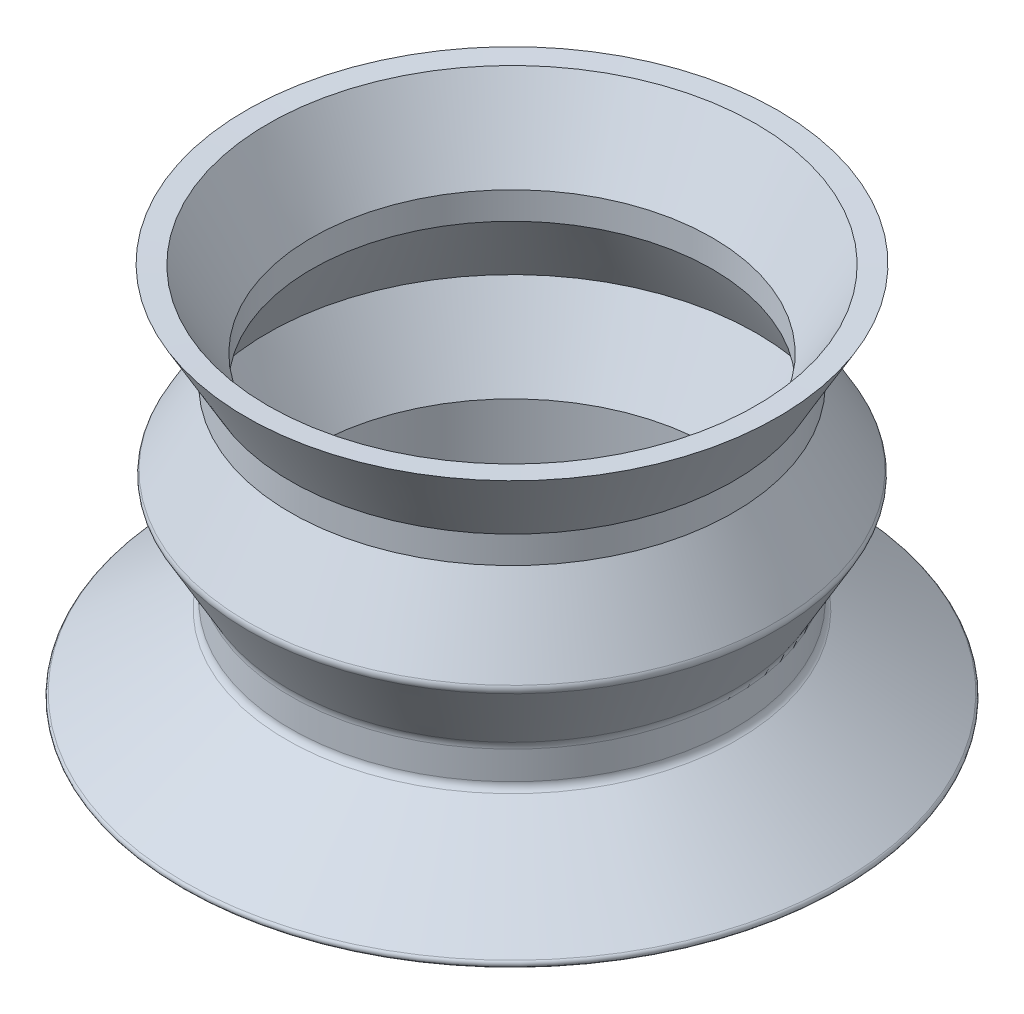
SolidWorks part; units mm, degrees
ref_plane "Front Plane" through (0, 0, 0) normal (0, 0, 1) x (1, 0, 0)
ref_plane "Top Plane" through (0, 0, 0) normal (0, 1, 0) x (1, 0, 0)
ref_plane "Right Plane" through (0, 0, 0) normal (1, 0, 0) x (0, 0, -1)
sketch "Sketch1" plane through (0, 0, 0) normal (0, 0, 1) x (1, 0, 0)
  line L0 (-18, 0) -> (-12, 4.2)
  line L1 (55, 0) -> (-55, 0) construction
  line L5 (-12, 4.2) -> (-11.6848, 3.2) construction
  line L7 (0, -55) -> (0, 55) construction
  line L8 (-18, 0) -> (-11.7545, -4.3719)
  line L12 (-12, 4.2) -> (0, 4.2) construction
  line L13 (-11.7545, -4.3719) -> (0, -4.3719) construction
  line L15 (-16.2562, 0) -> (-11.6848, 3.2)
  line L16 (-11.6848, 3.2) -> (0, 3.2) construction
  line L17 (-16.2562, 0) -> (-11.4393, -3.3719) construction
  line L18 (-11.4393, -3.3719) -> (0, -3.3719) construction
  line L19 (0, 4.2) -> (0, 3.2) construction
  line L20 (-16.2562, 0) -> (-11.4393, -3.3719)
  line L21 (-11.4393, -3.3719) -> (0, -3.3719) construction
  line L22 (-11.4393, -3.3719) -> (-11.7545, -4.3719)
  line L23 (-12, 4.2) -> (-12, 6.2)
  line L24 (-16.2562, 0) -> (-11.6848, 3.2) construction
  line L25 (0, -3.3719) -> (0, -4.3719) construction
  line L27 (-10.8755, 6.2476) -> (-10.8755, 3.2)
  line L28 (-10.8755, 3.2) -> (-11.6848, 3.2)
  line L29 (-10.8755, 3.2) -> (-10.8755, -7.0879) construction
  line L30 (-14.4, 10.4) -> (-12, 6.2)
  line L31 (-14.4, 10.4) -> (-12, 14.6)
  line L32 (-13.2482, 10.4) -> (-10.8755, 6.2476)
  line L33 (-13.2482, 10.4) -> (-10.8482, 14.6)
  line L34 (0, 16.9201) -> (0, 4.5742) construction
  line L35 (-10.8482, 14.6) -> (-10.8482, 16.0759)
  line L37 (-12, 16.0759) -> (-12, 14.6)
  line L38 (-13.221, 20.2283) -> (-10.8482, 16.0759)
  line L39 (-14.4, 20.2759) -> (-12, 16.0759)
  line L40 (-14.4, 20.2759) -> (-13.221, 20.2283)
  point P7 (0, -4.3719)
  point P10 (0, 4.2)
  dimension "D2" = 4.2
  dimension "D3" = 1
  dimension "D4" = 18
  dimension "D6" = 12
  dimension "D7" = 2
  dimension "D8" = 1
  dimension "D9" = 4.2
  dimension "D10" = 12
  dimension "D11" = 14.4
  dimension "D12" = 1
  dimension "D13" = 1.1245
  dimension "D5" = 1
ref_axis "Axis1" through (0, -8.65, 0) along (0, 1, 0)
revolve "Revolve1" add sketch "Sketch1" angle 360 about axis through (0, -8.65, 0) along (0, 1, 0)
fillet "fillet_out_low" radius 0.2 1 edges at (0, 0, -18)
fillet "Fillet_active_low" radius 0.5 1 edges at (0, 4.2, -12)
fillet "Fillet5" radius 0.4 1 edges at (0, 10.4, -14.4)
fillet "Fillet6" radius 0.8 1 edges at (0, 6.2, -12)
